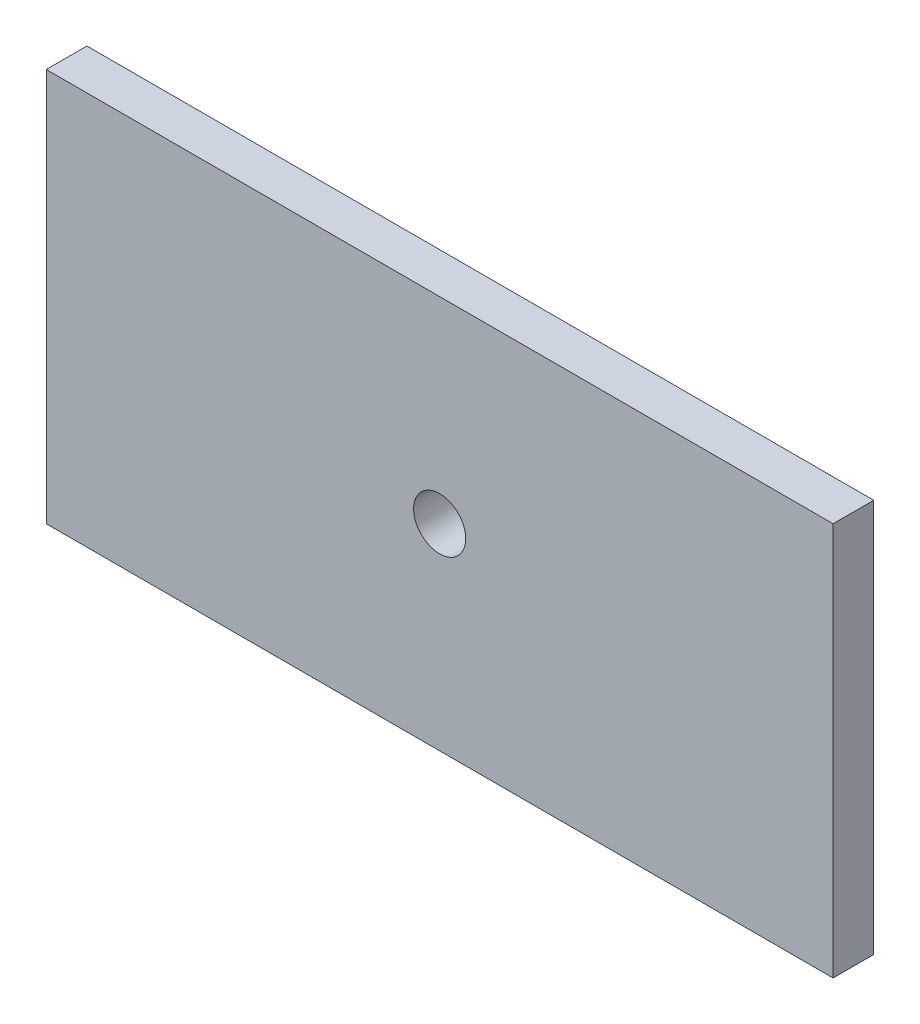
SolidWorks part; units mm, degrees
ref_plane "Front Plane" through (0, 0, 0) normal (0, 0, 1) x (1, 0, 0)
ref_plane "Top Plane" through (0, 0, 0) normal (0, 1, 0) x (1, 0, 0)
ref_plane "Right Plane" through (0, 0, 0) normal (1, 0, 0) x (0, 0, -1)
sketch "Sketch1" plane through (0, 0, 0) normal (0, 0, 1) x (1, 0, 0)
  line L1 (-76.2, -38.1) -> (76.2, -38.1)
  line L2 (-76.2, -38.1) -> (-76.2, 38.1)
  line L3 (-76.2, 38.1) -> (76.2, 38.1)
  line L4 (76.2, -38.1) -> (76.2, 38.1)
  line L5 (-76.2, -38.1) -> (76.2, 38.1) construction
  line L6 (-76.2, 38.1) -> (76.2, -38.1) construction
  point P0 (0, 0)
  dimension "D1" = 152.4
  dimension "D2" = 76.2
extrude "Boss-Extrude1" add sketch "Sketch1" against normal blind 7.874
sketch "Sketch2" plane through (0, 0, 0) normal (0, 0, 1) x (1, 0, 0)
  circle A0 centre (0, 0) radius 5.05
extrude "Cut-Extrude1" cut sketch "Sketch2" against normal blind 7.874
